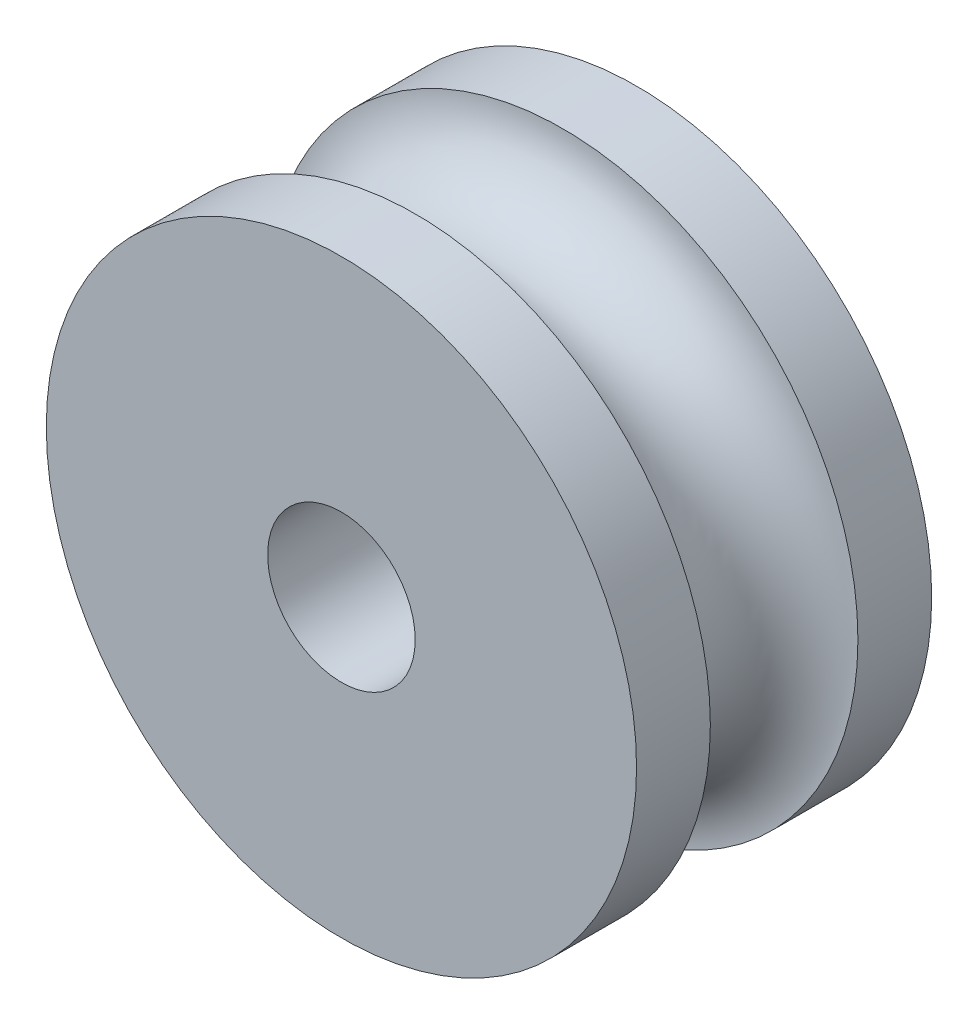
SolidWorks part; units mm, degrees
ref_plane "Front Plane" through (0, 0, 0) normal (0, 0, 1) x (1, 0, 0)
ref_plane "Top Plane" through (0, 0, 0) normal (0, 1, 0) x (1, 0, 0)
ref_plane "Right Plane" through (0, 0, 0) normal (1, 0, 0) x (0, 0, -1)
sketch "Sketch1" plane through (0, 0, 0) normal (0, 0, 1) x (1, 0, 0)
  circle A0 centre (0, 0) radius 40
  circle A1 centre (0, 0) radius 10
  dimension "D1" = 80
  dimension "D2" = 20
extrude "Boss-Extrude1" add sketch "Sketch1" along normal blind 40 contours A0 A1
sketch "Sketch2" plane through (0, 0, 0) normal (0, 1, 0) x (1, 0, 0)
  line L0 (-40, 0) -> (-40, -40) construction
  line L1 (0, 0) -> (0, -40) construction
  line L2 (-40, -40) -> (40, -40) construction
  circle A0 centre (-40, -20) radius 10
  dimension "D1" = 20
revolve "Cut-Revolve1" cut sketch "Sketch2" angle 360 about L1
